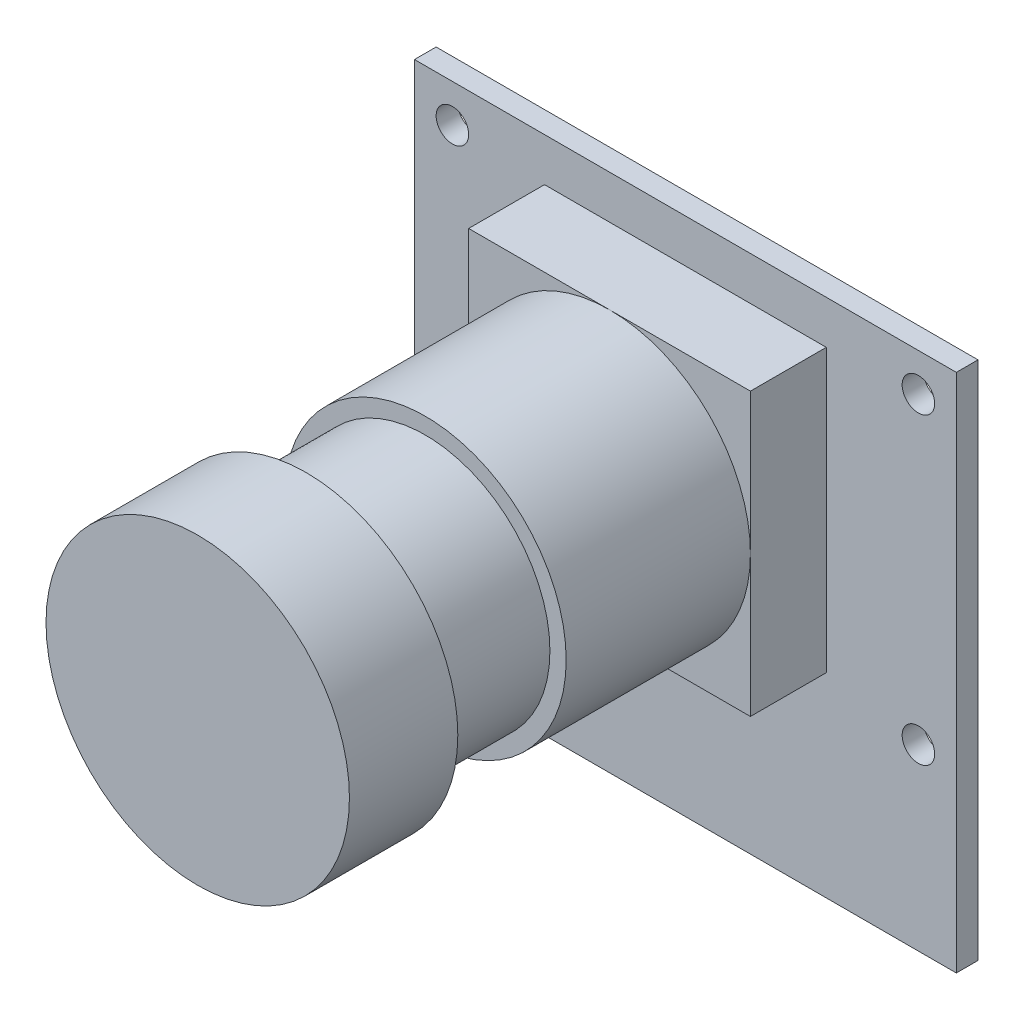
SolidWorks part; units mm, degrees
ref_plane "前视基准面" through (0, 0, 0) normal (0, 0, 1) x (1, 0, 0)
ref_plane "上视基准面" through (0, 0, 0) normal (0, 1, 0) x (1, 0, 0)
ref_plane "右视基准面" through (0, 0, 0) normal (1, 0, 0) x (0, 0, -1)
other "Configuration Table"
sketch "草图1" plane through (0, 0, 0) normal (0, 0, 1) x (1, 0, 0)
  line L1 (-12.5, -12) -> (12.5, -12)
  line L2 (-12.5, -12) -> (-12.5, 12)
  line L3 (-12.5, 12) -> (12.5, 12)
  line L4 (12.5, -12) -> (12.5, 12)
  line L5 (0, 12) -> (0, -12) construction
  line L6 (-12.5, 0) -> (12.5, 0) construction
  point P0 (0, 0)
  dimension "D1" = 24
  dimension "D2" = 25
extrude "凸台-拉伸1" add sketch "草图1" along normal blind 1
sketch "草图2" plane through (0, 0, 1) normal (0, 0, 1) x (1, 0, 0)
  line L0 (12.5, 12) -> (-12.5, 12) construction
  line L1 (-6.5, 10) -> (6.5, 10)
  line L2 (-6.5, 10) -> (-6.5, -3)
  line L3 (-6.5, -3) -> (6.5, -3)
  line L4 (6.5, 10) -> (6.5, -3)
  line L5 (0, 10) -> (0, 0) construction
  dimension "D1" = 13
  dimension "D2" = 2
extrude "凸台-拉伸2" add sketch "草图2" along normal blind 3.5
sketch "草图3" plane through (0, 0, 4.5) normal (0, 0, 1) x (1, 0, 0)
  line L0 (-6.5, -3) -> (6.5, -3) construction
  line L2 (6.5, 10) -> (-6.5, 10) construction
  line L3 (-6.5, 10) -> (-6.5, -3) construction
  circle A0 centre (0, 3.5) radius 6.5
extrude "凸台-拉伸3" add sketch "草图3" along normal blind 8.5
sketch "草图4" plane through (0, 0, 13) normal (0, 0, 1) x (1, 0, 0)
  circle A0 centre (0, 3.5) radius 5.75
  circle A1 centre (0, 3.5) radius 6.5 construction
  dimension "D1" = 11.5
extrude "凸台-拉伸4" add sketch "草图4" along normal blind 5.5
sketch "草图5" plane through (0, 0, 18.5) normal (0, 0, 1) x (1, 0, 0)
  circle A0 centre (0, 3.5) radius 7
  circle A1 centre (0, 3.5) radius 5.75 construction
  dimension "D1" = 14
extrude "凸台-拉伸5" add sketch "草图5" along normal blind 5
sketch "草图6" plane through (0, 0, 1) normal (0, 0, 1) x (1, 0, 0)
  line L0 (12.5, -12) -> (12.5, 12) construction
  line L1 (-12.5, 12) -> (-12.5, -12) construction
  line L2 (12.5, 12) -> (-12.5, 12) construction
  line L3 (-12.5, -12) -> (12.5, -12) construction
  circle A0 centre (10.75, 10.25) radius 0.75
  circle A1 centre (10.75, -3.75) radius 0.75
  circle A2 centre (-10.75, 10.25) radius 0.75
  circle A3 centre (-10.75, -3.75) radius 0.75
  point P10 (0, 0)
  point P17 (0, 0)
  point P18 (0, 0)
  dimension "D2" = 1.5
  dimension "D1" = 1.75
  dimension "D3" = 1.75
  dimension "D4" = 1.75
  dimension "D5" = 1.75
  dimension "D6" = 8.25
  dimension "D7" = 8.25
extrude "切除-拉伸1" cut sketch "草图6" against normal up to surface (1 mm away) up to face at (0, 0, 0)
sketch "草图7" plane through (0, 0, 0) normal (0, 0, -1) x (-1, 0, 0)
  line L0 (12.5, -12) -> (-12.5, -12) construction
  line L1 (-7.15, -12) -> (7.15, -12)
  line L2 (-7.15, -12) -> (-7.15, -6.5)
  line L3 (-7.15, -6.5) -> (7.15, -6.5)
  line L4 (7.15, -12) -> (7.15, -6.5)
  line L5 (0, -12) -> (0, -6.5) construction
  dimension "D1" = 5.5
  dimension "D2" = 14.3
extrude "凸台-拉伸6" add sketch "草图7" along normal blind 2
